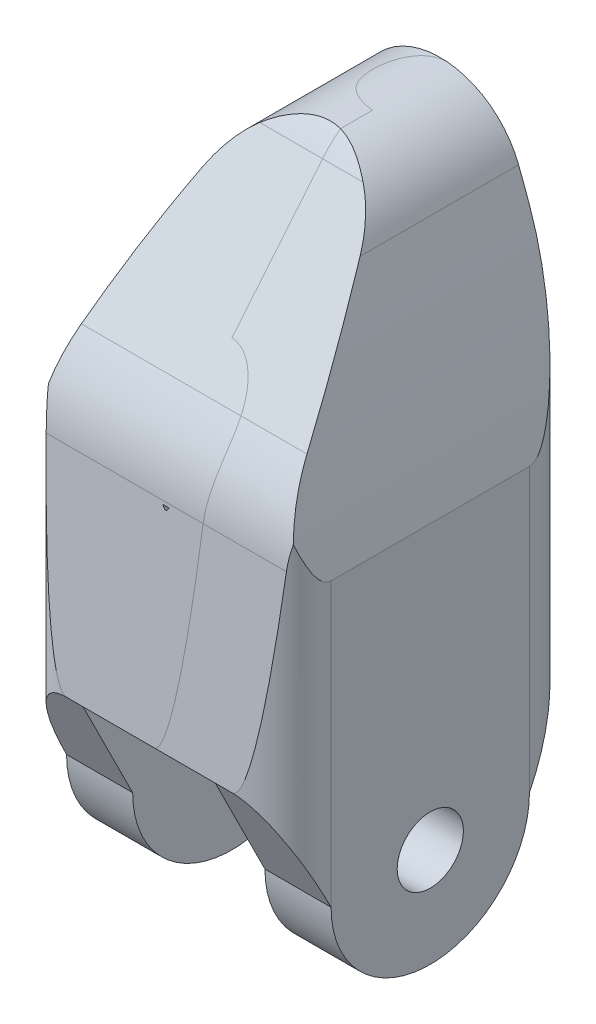
SolidWorks part; units mm, degrees
ref_plane "Front Plane" through (0, 0, 0) normal (0, 0, 1) x (1, 0, 0)
ref_plane "Top Plane" through (0, 0, 0) normal (0, 1, 0) x (1, 0, 0)
ref_plane "Right Plane" through (0, 0, 0) normal (1, 0, 0) x (0, 0, -1)
sketch "Sketch1" plane through (0, 0, 0) normal (0, 1, 0) x (1, 0, 0)
  line L0 (-20.32, 27.0953) -> (-20.32, 11.8553)
  line L1 (0, 27.0953) -> (0, 11.8553)
  line L2 (-16.51, 8.0453) -> (-3.81, 8.0453)
  line L3 (-16.51, 30.9053) -> (-3.81, 30.9053)
  arc A0 (-20.32, 11.8553) -> (-16.51, 8.0453) centre (-16.51, 11.8553) ccw
  arc A1 (-3.81, 8.0453) -> (0, 11.8553) centre (-3.81, 11.8553) ccw
  arc A2 (-20.32, 27.0953) -> (-16.51, 30.9053) centre (-16.51, 27.0953) cw
  arc A3 (0, 27.0953) -> (-3.81, 30.9053) centre (-3.81, 27.0953) ccw
  dimension "D1" = 15.24
  dimension "D2" = 20.32
  dimension "D3" = 22.86
extrude "Boss-Extrude1" add sketch "Sketch1" along normal blind 50.8
sketch "Sketch3" plane through (0, 50.8, 0) normal (0, 1, 0) x (1, 0, 0)
  line L0 (-10.16, 10.5853) -> (-10.16, 28.3653) construction
  line L1 (-16.51, 8.0453) -> (-3.81, 8.0453) construction
  line L2 (-3.81, 30.9053) -> (-16.51, 30.9053) construction
  line L3 (0, 11.8553) -> (0, 27.0953) construction
  circle A0 centre (-10.16, 10.5853) radius 1.27
  circle A1 centre (-10.16, 28.3653) radius 1.27
  dimension "D2" = 2.54
  dimension "D1" = 17.78
  dimension "D3" = 10.16
  dimension "D4" = 2.54
extrude "Cut-Extrude2" cut sketch "Sketch3" against normal blind 50.8 from offset 20.32 offset against normal yes
sketch "Sketch2" plane through (-20.32, 0, 0) normal (-1, 0, 0) x (0, 0, 1)
  line L0 (-27.0953, 7.62) -> (-30.9053, 15.24)
  line L1 (-27.0953, 50.8) -> (-27.0953, 0) construction
  line L2 (-30.9053, 15.24) -> (-30.9053, -5.08)
  line L4 (-8.0453, -5.08) -> (-8.0453, 15.24)
  line L5 (-8.0453, 15.24) -> (-11.8553, 7.62)
  line L6 (-11.8553, 50.8) -> (-11.8553, 0) construction
  line L8 (-27.0953, 0) -> (-11.8553, 0) construction
  line L9 (-30.9053, -5.08) -> (-8.0453, -5.08)
  line L10 (-30.9053, 50.8) -> (-30.9053, 0) construction
  line L11 (-8.0453, 50.8) -> (-8.0453, 0) construction
  arc A0 (-11.8553, 7.62) -> (-27.0953, 7.62) centre (-19.4753, 7.62) cw
  dimension "D1" = 20.32
  dimension "D2" = 5.08
extrude "Cut-Extrude1" cut sketch "Sketch2" against normal blind 50.8
sketch "Sketch4" plane through (0, 0, -8.0453) normal (0, 0, 1) x (1, 0, 0)
  line L0 (-15.24, 15.24) -> (-15.24, 0)
  line L1 (-15.24, 0) -> (-5.08, 0)
  line L2 (-5.08, 0) -> (-5.08, 15.24)
  line L3 (-5.08, 15.24) -> (-15.24, 15.24)
  line L4 (0, 0) -> (0, 7.62) construction
  dimension "D1" = 10.16
  dimension "D2" = 5.08
  dimension "D3" = 15.24
extrude "Cut-Extrude3" cut sketch "Sketch4" against normal blind 50.8
sketch "Sketch5" plane through (-20.32, 0, 0) normal (-1, 0, 0) x (0, 0, 1)
  line L0 (-27.0953, 50.8) -> (-27.0953, 7.62) construction
  circle A0 centre (-19.4753, 7.62) radius 2.54
  arc A1 (-27.0953, 7.62) -> (-11.8553, 7.62) centre (-19.4753, 7.62) ccw construction
  point P5 (-19.4753, 0)
  dimension "D3" = 5.08
  dimension "D1" = 7.62
  dimension "D2" = 7.62
extrude "Cut-Extrude5" cut sketch "Sketch5" against normal blind 50.8
sketch "Sketch6" plane through (-20.32, 0, 0) normal (-1, 0, 0) x (0, 0, 1)
  line L0 (-11.8553, 36.8468) -> (-21.0123, 47.9345)
  line L1 (-27.0953, 50.8) -> (-11.8553, 50.8) construction
  line L2 (-27.0953, 50.8) -> (-31.5254, 50.8)
  line L3 (-11.8553, 50.8) -> (-11.8553, 7.62) construction
  line L4 (-31.5254, 50.8) -> (-31.5254, 15.0885)
  line L5 (-8.0453, 15.24) -> (-9.3575, 30.7255)
  line L6 (-31.5254, 15.0885) -> (-40.3927, 51.9343)
  line L7 (-40.3927, 51.9343) -> (12.2737, 71.2613)
  line L8 (12.2737, 71.2613) -> (-8.0453, 15.24)
  arc A0 (-11.8553, 36.8468) -> (-9.3575, 30.7255) centre (-20.4002, 29.7898) cw
  arc A1 (-21.0123, 47.9345) -> (-27.0953, 50.8) centre (-27.0953, 42.9107) ccw
extrude "Cut-Extrude6" cut sketch "Sketch6" against normal blind 32.512
sketch "Sketch7" plane through (0, 0, -30.9053) normal (0, 0, -1) x (-1, 0, 0)
  line L0 (0, 29.3352) -> (-12.8523, 67.8048)
  line L1 (-12.8523, 67.8048) -> (37.5949, 66.8616)
  line L2 (37.5949, 66.8616) -> (20.32, 29.3352)
  line L3 (0, 50.8) -> (0, 7.62) construction
  line L4 (20.32, 50.8) -> (20.32, 7.62) construction
  arc A0 (0, 29.3352) -> (4.6436, 45.1708) centre (97.9606, 9.2079) cw
  arc A1 (4.6436, 45.1708) -> (16.6823, 45.1708) centre (10.663, 42.851) cw
  arc A2 (16.6823, 45.1708) -> (20.32, 29.3352) centre (-36.8657, 24.5342) cw
extrude "Cut-Extrude7" cut sketch "Sketch7" against normal blind 32.512
sketch "Sketch8" plane through (0, 15.24, 0) normal (0, -1, 0) x (1, 0, 0)
  line L0 (-9.8095, -14.045) -> (-9.8095, -24.843)
  line L1 (-5.08, -8.0453) -> (-15.24, -8.0453) construction
  line L2 (-5.08, -30.9053) -> (-15.24, -30.9053) construction
  arc A0 (-9.8095, -14.045) -> (-9.8095, -8.0453) centre (-9.8095, -11.0452) ccw
  arc A1 (-9.8095, -24.843) -> (-10.16, -30.9053) centre (-9.8095, -27.8843) ccw
  point P10 (0, 0)
split line "Split Line1"
